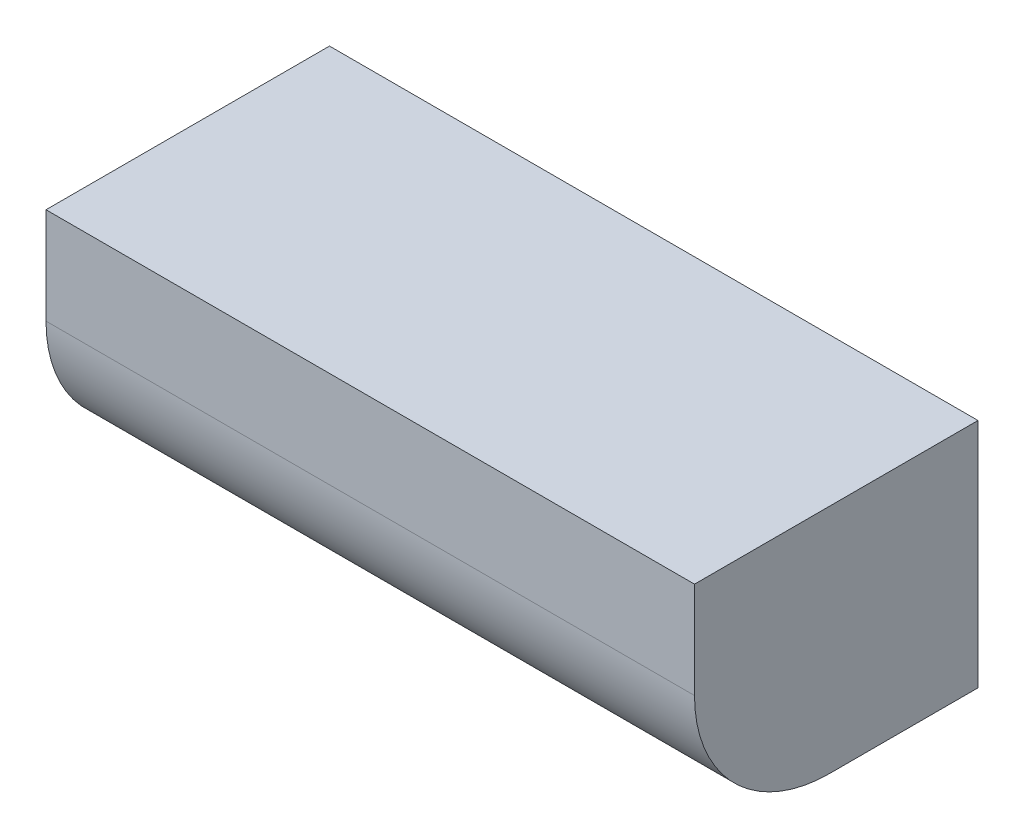
SolidWorks part; units mm, degrees
ref_plane "Front Plane" through (0, 0, 0) normal (0, 0, 1) x (1, 0, 0)
ref_plane "Top Plane" through (0, 0, 0) normal (0, 1, 0) x (1, 0, 0)
ref_plane "Right Plane" through (0, 0, 0) normal (1, 0, 0) x (0, 0, -1)
sketch "Sketch1" plane through (0, 0, 0) normal (0, 0, 1) x (1, 0, 0)
  line L1 (0, 0) -> (48, 0)
  line L2 (0, 0) -> (0, 53)
  line L3 (0, 53) -> (48, 53)
  line L4 (48, 0) -> (48, 53)
  dimension "D1" = 53
  dimension "D2" = 48
extrude "Boss-Extrude1" add sketch "Sketch1" along normal blind 10
sketch "Sketch2" plane through (0, 0, 0) normal (0, 0, -1) x (-1, 0, 0)
  line L0 (0, 53) -> (0, 0) construction
  line L1 (-48, 0) -> (0, 0)
  line L2 (-48, 0) -> (-48, -5.6163)
  line L3 (-48, -5.6163) -> (0, -5.6163)
  line L4 (0, 0) -> (0, -5.6163)
  dimension "D1" = 5.6163
extrude "Boss-Extrude2" add sketch "Sketch2" against normal blind 33.1918
sketch "Sketch4" plane through (0, 0, 10) normal (0, 0, 1) x (1, 0, 0)
  line L1 (0, 53) -> (4, 53)
  line L2 (0, 53) -> (0, 43)
  line L3 (0, 43) -> (4, 43)
  line L4 (4, 53) -> (4, 43)
  line L5 (48, 53) -> (44, 53)
  line L6 (48, 53) -> (48, 43)
  line L7 (48, 43) -> (44, 43)
  line L8 (44, 53) -> (44, 43)
  dimension "D1" = 10
  dimension "D2" = 4
extrude "Boss-Extrude4" add sketch "Sketch4" along normal blind 40
sketch "Sketch5" plane through (0, 0, 10) normal (0, 0, 1) x (1, 0, 0)
  line L0 (48, 0) -> (48, 43) construction
  line L1 (0, 0) -> (48, 0)
  line L2 (0, 0) -> (0, 10.8609)
  line L3 (0, 10.8609) -> (48, 10.8609)
  line L4 (48, 0) -> (48, 10.8609)
  dimension "D1" = 10.8609
extrude "Boss-Extrude5" add sketch "Sketch5" along normal up to surface (23.1918 mm away) up to face at (24, -2.8082, 33.1918)
sketch "Sketch6" plane through (0, -5.6163, 0) normal (0, -1, 0) x (1, 0, 0)
  line L0 (0, 0) -> (0, 28.1918) construction
  line L1 (0, 33.1918) -> (0, 0) construction
  line L2 (48, 33.1918) -> (48, 0) construction
  line L3 (0, 28.1918) -> (48, 28.1918)
  line L4 (0, 28.1918) -> (0, 33.1918)
  line L5 (0, 33.1918) -> (48, 33.1918)
  line L6 (48, 28.1918) -> (48, 33.1918)
  line L8 (48, 33.1918) -> (0, 33.1918) construction
  dimension "D2" = 5
extrude "Boss-Extrude6" add sketch "Sketch6" along normal blind 42.3
sketch "Sketch7" plane through (0, 0, 0) normal (-1, 0, 0) x (0, 0, 1)
  line L0 (33.1918, 10.8609) -> (10, 10.8609) construction
  line L1 (0, -5.6163) -> (-12.8082, -5.6163)
  line L2 (0, -5.6163) -> (0, 10.8609)
  line L3 (0, 10.8609) -> (-12.8082, 10.8609)
  line L4 (-12.8082, -5.6163) -> (-12.8082, 10.8609)
  line L5 (28.1918, -47.9163) -> (28.1918, -5.6163) construction
  dimension "D1" = 41
extrude "Boss-Extrude7" add sketch "Sketch7" against normal up to surface (48 mm away) up to face at (48, 10.6657, 24.2767)
sketch "Sketch8" plane through (0, 0, 28.1918) normal (0, 0, -1) x (-1, 0, 0)
  line L0 (-24, -26.6163) -> (-24, -5.6163) construction
  line L1 (0, -5.6163) -> (-48, -5.6163) construction
  line L3 (-8.5, -42.1163) -> (-39.5, -42.1163) construction
  line L4 (-8.5, -42.1163) -> (-8.5, -11.1163) construction
  line L5 (-8.5, -11.1163) -> (-39.5, -11.1163) construction
  line L6 (-39.5, -42.1163) -> (-39.5, -11.1163) construction
  line L7 (-8.5, -42.1163) -> (-39.5, -11.1163) construction
  line L8 (-8.5, -11.1163) -> (-39.5, -42.1163) construction
  circle A0 centre (-24, -26.6163) radius 11.5
  circle A1 centre (-39.5, -11.1163) radius 2
  circle A2 centre (-39.5, -42.1163) radius 2
  circle A3 centre (-8.5, -11.1163) radius 2
  circle A4 centre (-8.5, -42.1163) radius 2
  dimension "D2" = 23
  dimension "D4" = 4
  dimension "D1" = 21
  dimension "D3" = 31
extrude "Cut-Extrude1" cut sketch "Sketch8" against normal up to next
fillet "Fillet1" radius 10 1 edges at (24, 10.8609, 0)
fillet "Fillet2" radius 4 2 edges at (2, 43, 10) (46, 43, 10)
sketch "Sketch9" plane through (48, 0, 0) normal (1, 0, 0) x (0, 0, -1)
  line L1 (12.8082, 10.8609) -> (17.8082, 10.8609)
  line L2 (12.8082, 10.8609) -> (12.8082, -5.6163)
  line L3 (12.8082, -5.6163) -> (17.8082, -5.6163)
  line L4 (17.8082, 10.8609) -> (17.8082, -5.6163)
  line L5 (-28.1918, -5.6163) -> (12.8082, -5.6163) construction
  dimension "D1" = 5
extrude "Boss-Extrude9" add sketch "Sketch9" against normal up to surface (48 mm away) contours L4 L3 L2 L1 up to face at (0, 13.3569, 15.8852)
sketch "Sketch10" plane through (0, 0, 10) normal (0, 0, 1) x (1, 0, 0)
  line L0 (4, 53) -> (9, 35) construction
  line L1 (9, 35) -> (39, 35) construction
  line L2 (39, 35) -> (44, 53) construction
  line L3 (44, 53) -> (4, 53) construction
  line L4 (44, 53) -> (44, 43) construction
  line L6 (12.429, 36.9797) -> (9, 38.9595)
  line L7 (9, 38.9595) -> (5.571, 36.9797)
  line L8 (5.571, 36.9797) -> (5.571, 33.0203)
  line L9 (5.571, 33.0203) -> (9, 31.0405)
  line L10 (9, 31.0405) -> (12.429, 33.0203)
  line L11 (12.429, 33.0203) -> (12.429, 36.9797)
  line L12 (35.571, 36.9797) -> (35.571, 33.0203)
  line L13 (35.571, 33.0203) -> (39, 31.0405)
  line L14 (39, 31.0405) -> (42.429, 33.0203)
  line L15 (42.429, 33.0203) -> (42.429, 36.9797)
  line L16 (42.429, 36.9797) -> (39, 38.9595)
  line L17 (39, 38.9595) -> (35.571, 36.9797)
  circle A0 centre (9, 35) radius 3.429 construction
  circle A1 centre (39, 35) radius 3.429 construction
  dimension "D1" = 6.858
  dimension "D2" = 30
  dimension "D3" = 18
extrude "Cut-Extrude2" cut sketch "Sketch10" against normal blind 6
sketch "Sketch11" plane through (0, 0, 4) normal (0, 0, 1) x (1, 0, 0)
  circle A0 centre (9, 35) radius 1.9304
  circle A1 centre (39, 35) radius 1.9304
  dimension "D1" = 3.8608
extrude "Cut-Extrude3" cut sketch "Sketch11" against normal blind 6
sketch "Sketch12" plane through (0, 53, 0) normal (0, 1, 0) x (1, 0, 0)
  line L0 (0, 0) -> (0, -50)
  line L1 (0, -50) -> (4, -50)
  line L2 (4, -50) -> (4, -10)
  line L3 (4, -10) -> (44, -10)
  line L4 (44, -10) -> (44, -50)
  line L5 (44, -50) -> (48, -50)
  line L6 (48, -50) -> (48, 0)
  line L7 (48, 0) -> (0, 0)
extrude "Boss-Extrude11" add sketch "Sketch12" along normal blind 3
sketch "Sketch13" plane through (48, 0, 0) normal (1, 0, 0) x (0, 0, -1)
  line L0 (0, 56) -> (0, 20.8609) construction
  line L1 (17.8082, 10.8609) -> (10, 10.8609)
  line L2 (17.8082, 10.8609) -> (17.8082, 28)
  line L3 (17.8082, 28) -> (0, 28)
  line L4 (0, 20.8609) -> (0, 28)
  arc A0 (0, 20.8609) -> (10, 10.8609) centre (10, 20.8609) ccw
  arc A1 (0, 20.8609) -> (10, 10.8609) centre (10, 20.8609) ccw construction
  dimension "D1" = 17.1391
extrude "Boss-Extrude12" add sketch "Sketch13" against normal up to surface (48 mm away) up to face at (0, 13.7855, 15.171)
sketch "Sketch14" plane through (48, 0, 0) normal (1, 0, 0) x (0, 0, -1)
  line L0 (0, 28) -> (0, 20.8609)
  line L1 (17.8082, 10.8609) -> (10, 10.8609)
  line L2 (0, 28) -> (17.8082, 28)
  line L3 (17.8082, 28) -> (17.8082, 10.8609)
  line L5 (-76.8161, -52.9018) -> (43.0088, -52.9018)
  line L6 (-76.8161, -52.9018) -> (-76.8161, 69.3357)
  line L7 (-76.8161, 69.3357) -> (43.0088, 69.3357)
  line L8 (43.0088, -52.9018) -> (43.0088, 69.3357)
  arc A0 (0, 20.8609) -> (10, 10.8609) centre (10, 20.8609) ccw
  arc A1 (0, 20.8609) -> (10, 10.8609) centre (10, 20.8609) ccw construction
extrude "Cut-Extrude4" cut sketch "Sketch14" against normal through all
sketch "Sketch15" plane through (0, 0, -17.8082) normal (0, 0, -1) x (-1, 0, 0)
  line L1 (0, 10.8609) -> (-48, 10.8609)
  line L2 (0, 10.8609) -> (0, 28)
  line L3 (0, 28) -> (-48, 28)
  line L4 (-48, 10.8609) -> (-48, 28)
extrude "Boss-Extrude13" add sketch "Sketch15" along normal blind 3.175
